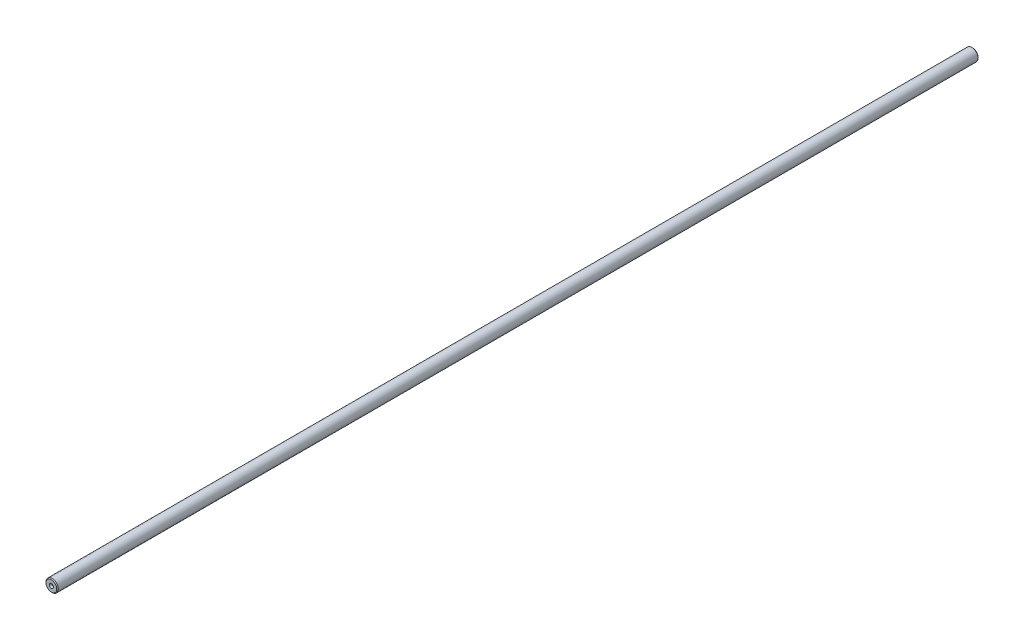
SolidWorks part; units mm, degrees
ref_plane "Front Plane" through (0, 0, 0) normal (0, 0, 1) x (1, 0, 0)
ref_plane "Top Plane" through (0, 0, 0) normal (0, 1, 0) x (1, 0, 0)
ref_plane "Right Plane" through (0, 0, 0) normal (1, 0, 0) x (0, 0, -1)
sketch "Sketch1" plane through (0, 0, 0) normal (0, 0, 1) x (1, 0, 0)
  circle A0 centre (0, 0) radius 8
  dimension "D1" = 16
extrude "Boss-Extrude1" add sketch "Sketch1" along normal mid plane 1200
cosmetic thread "Cosmetic Thread1" parameters "D2"=15
hole_wizard "CSK for M2.5 Flat Head Machine Screw1" positions "Sketch3" profile "Sketch4" countersink size "M2.5" standard "ANSI Metric"
sketch "Sketch3" plane through (0, 0, -600) normal (0, 0, -1) x (-1, 0, 0)
  point P0 (0, 0)
sketch "Sketch4" plane through (0, 0, -600) normal (1, 0, 0) x (0, 1, 0)
  line L0 (0, 0) -> (0, 5)
  line L1 (0, 5) -> (1.45, 4.1288)
  line L2 (1.45, 4.1288) -> (1.45, 2.2517)
  line L3 (1.45, 2.2517) -> (2.75, 0)
  line L5 (2.75, 0) -> (0, 0)
  line L6 (-1.45, 2.2517) -> (-2.75, 0) construction
  line L10 (0, 5) -> (-1.45, 4.1288) construction
  line L11 (0, -6.35) -> (0, 107.95) construction
  dimension "Hole Dia." = 2.9
  dimension "Hole Depth" = 5
  dimension "Near C'Sink Dia." = 5.5
  dimension "Near C'Sink Angle" = 60
  dimension "Drill Angle" = 118
mirror "Mirror1" about plane through (0, 0, 0) normal (0, 0, 1) of "CSK for M2.5 Flat Head Machine Screw1"
chamfer "Chamfer1" distance 1 angle 45 2 edges at (8, 0, 600) (8, 0, -600)
